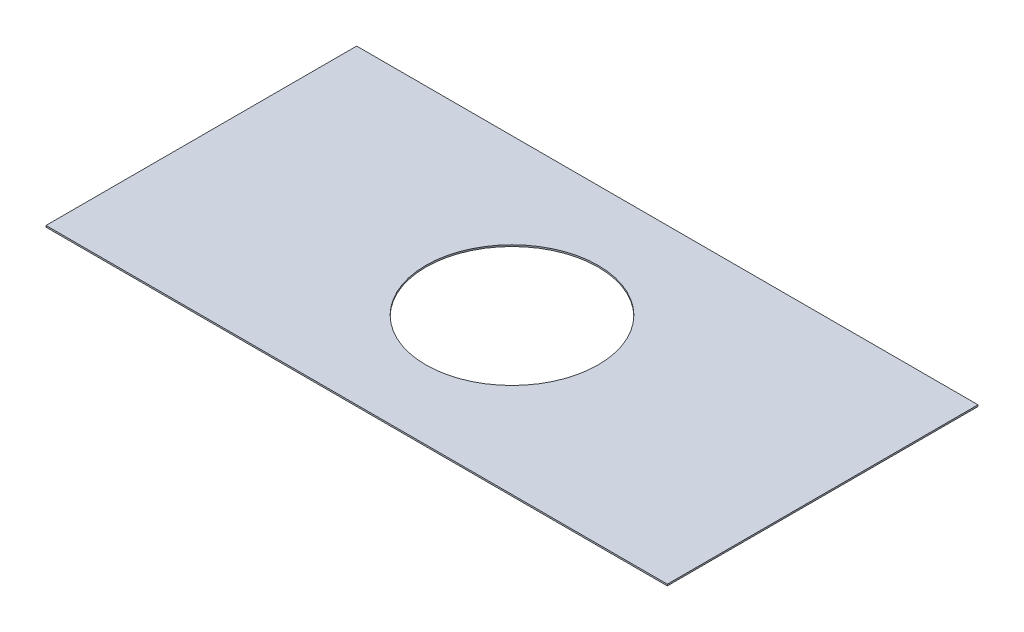
SolidWorks part; units mm, degrees
ref_plane "Front Plane" through (0, 0, 0) normal (0, 0, 1) x (1, 0, 0)
ref_plane "Top Plane" through (0, 0, 0) normal (0, 1, 0) x (1, 0, 0)
ref_plane "Right Plane" through (0, 0, 0) normal (1, 0, 0) x (0, 0, -1)
sketch "Sketch1" plane through (0, 0, 0) normal (0, 1, 0) x (1, 0, 0)
  line L1 (-20, 10) -> (20, 10)
  line L2 (-20, 10) -> (-20, -10)
  line L3 (-20, -10) -> (20, -10)
  line L4 (20, 10) -> (20, -10)
  line L5 (-20, 10) -> (20, -10) construction
  line L6 (-20, -10) -> (20, 10) construction
  circle A0 centre (0, 0) radius 5.5489
  point P0 (0, 0)
extrude "Boss-Extrude1" add sketch "Sketch1" along normal blind 0.1
